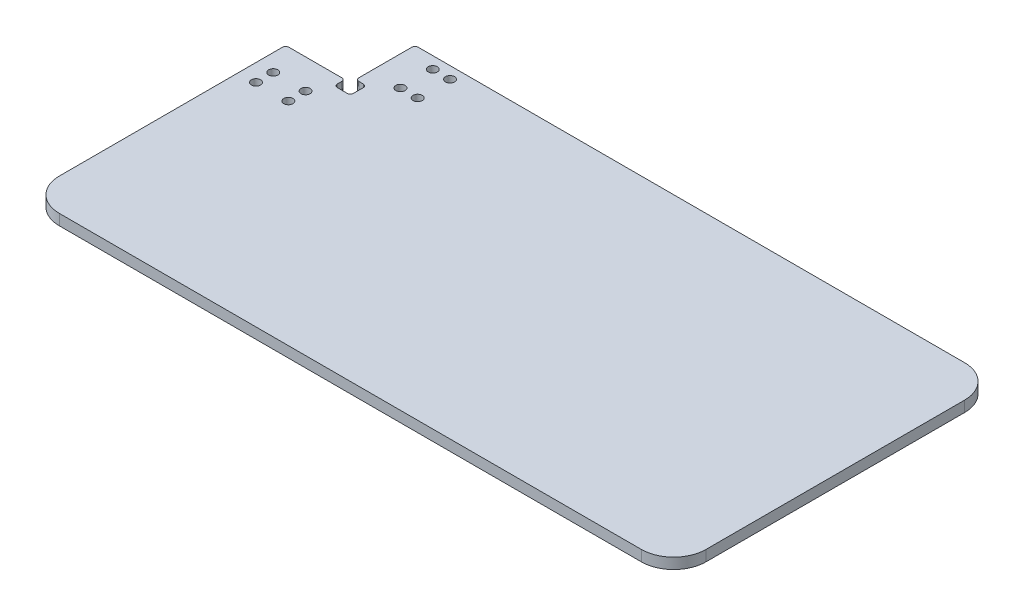
SolidWorks part; units mm, degrees
ref_plane "前视基准面" through (0, 0, 0) normal (0, 0, 1) x (1, 0, 0)
ref_plane "上视基准面" through (0, 0, 0) normal (0, 1, 0) x (1, 0, 0)
ref_plane "右视基准面" through (0, 0, 0) normal (1, 0, 0) x (0, 0, -1)
other "Configuration Table"
sketch "草图1" plane through (0, 0, 0) normal (0, 1, 0) x (1, 0, 0)
  line L0 (60, 0) -> (60, -55)
  line L1 (60, 0) -> (600, 0)
  line L2 (0, -60) -> (0, -300)
  line L3 (0, -300) -> (600, -300)
  line L4 (600, 0) -> (600, -300)
  line L5 (55, -60) -> (0, -60)
  line L6 (60, -55) -> (70, -55)
  line L7 (70, -55) -> (70, -70)
  line L8 (70, -70) -> (55, -70)
  line L9 (55, -70) -> (55, -60)
  line L10 (0, 0) -> (166.1856, -166.1856) construction
  circle A0 centre (103.5, -11) radius 4.25
  circle A1 centre (87.5, -11) radius 4.25
  circle A2 centre (103.5, -41) radius 4.25
  circle A3 centre (87.5, -41) radius 4.25
  circle A8 centre (16, -87.5) radius 4.25
  circle A9 centre (46, -87.5) radius 4.25
  circle A10 centre (16, -103.5) radius 4.25
  circle A11 centre (46, -103.5) radius 4.25
  point P4 (65, -55)
  dimension "D5" = 8.5
  dimension "D15" = 8.5
  dimension "D1" = 300
  dimension "D2" = 600
  dimension "D3" = 60
  dimension "D4" = 60
  dimension "D6" = 43.5
  dimension "D7" = 30
  dimension "D8" = 14
  dimension "D9" = 10
  dimension "D10" = 15
  dimension "D11" = 10
  dimension "D12" = 15
  dimension "D13" = 16
  dimension "D14" = 45
  dimension "D16" = 43.5
  dimension "D17" = 30
  dimension "D18" = 14
  dimension "D19" = 16
extrude "凸台-拉伸1" add sketch "草图1" along normal blind 10
fillet "圆角1" radius 30 3 edges at (600, 5, 0) (0, 5, 300) (600, 5, 300)
fillet "圆角2" radius 3 7 edges at (70, 5, 55) (70, 5, 70) (55, 5, 70) (55, 5, 60) (60, 5, 55) (60, 5, 0) (0, 5, 60)
